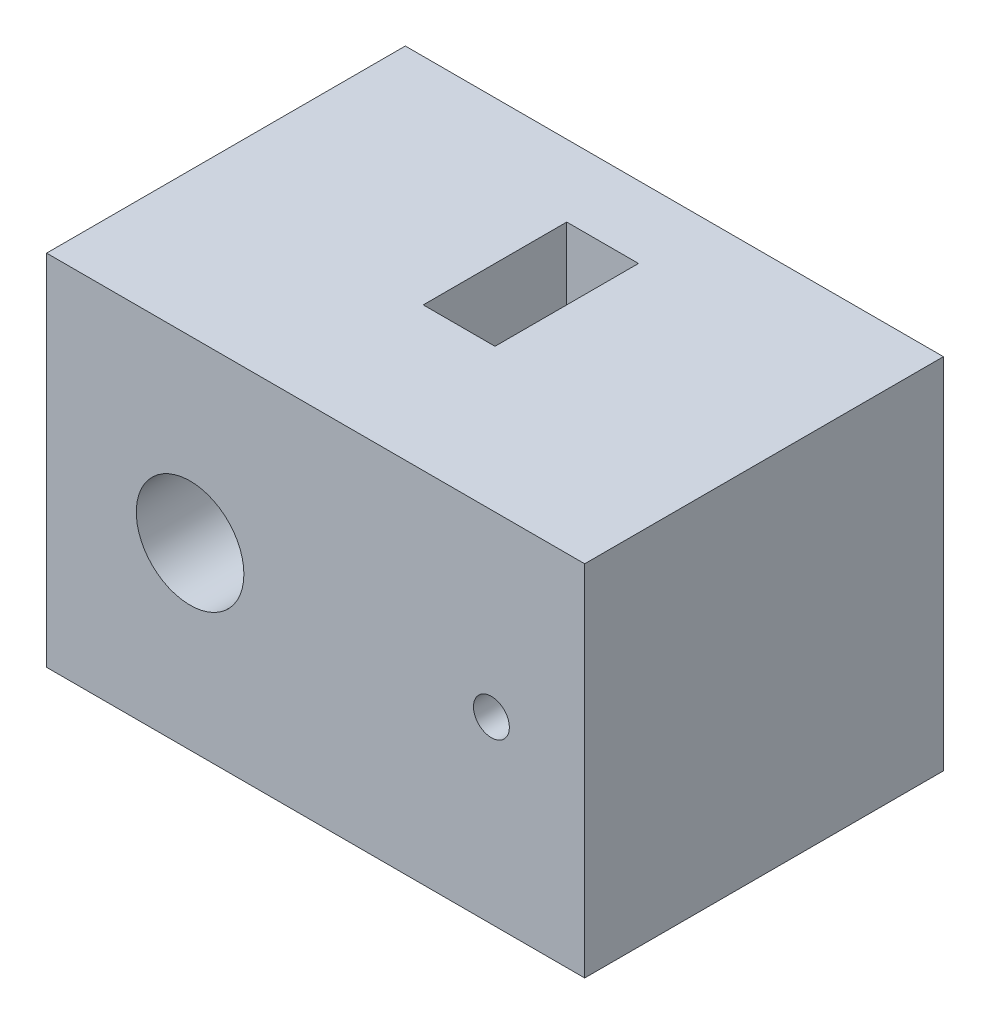
SolidWorks part; units mm, degrees
ref_plane "Front Plane" through (0, 0, 0) normal (0, 0, 1) x (1, 0, 0)
ref_plane "Top Plane" through (0, 0, 0) normal (0, 1, 0) x (1, 0, 0)
ref_plane "Right Plane" through (0, 0, 0) normal (1, 0, 0) x (0, 0, -1)
sketch "Sketch1" plane through (0, 0, 0) normal (0, 0, 1) x (1, 0, 0)
  line L1 (0, 0) -> (75, 0)
  line L2 (0, 0) -> (0, 50)
  line L3 (0, 50) -> (75, 50)
  line L4 (75, 0) -> (75, 50)
  circle A0 centre (20, 25) radius 7.5
  circle A1 centre (62, 25) radius 2.5
  dimension "D3" = 15
  dimension "D4" = 5
  dimension "D1" = 50
  dimension "D2" = 75
  dimension "D5" = 20
  dimension "D6" = 25
  dimension "D7" = 42
  dimension "D8" = 25
extrude "Boss-Extrude1" add sketch "Sketch1" along normal blind 50
sketch "Sketch2" plane through (0, 50, 0) normal (0, 1, 0) x (1, 0, 0)
  line L0 (75, 0) -> (0, 0) construction
  line L1 (32.5, -10) -> (42.5, -10)
  line L2 (32.5, -10) -> (32.5, -30)
  line L3 (32.5, -30) -> (42.5, -30)
  line L4 (42.5, -10) -> (42.5, -30)
  line L5 (37.5, -10) -> (37.5, -30) construction
  line L6 (37.5, 0) -> (37.5, -50) construction
  line L7 (75, -50) -> (0, -50) construction
  dimension "D1" = 10
  dimension "D2" = 20
  dimension "D3" = 5
extrude "Cut-Extrude1" cut sketch "Sketch2" against normal through all
